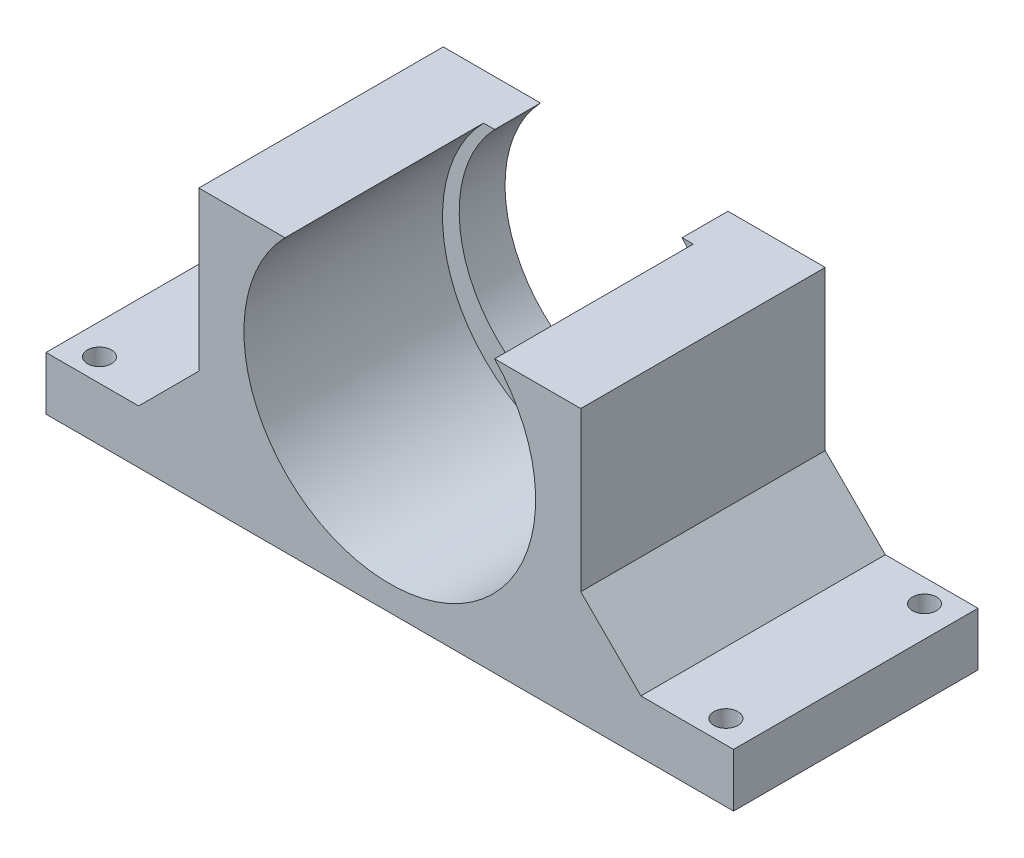
SolidWorks part; units mm, degrees
material "PF"
ref_plane "Front Plane" through (0, 0, 0) normal (0, 0, 1) x (1, 0, 0)
ref_plane "Top Plane" through (0, 0, 0) normal (0, 1, 0) x (1, 0, 0)
ref_plane "Right Plane" through (0, 0, 0) normal (1, 0, 0) x (0, 0, -1)
sketch "Sketch1" plane through (0, 0, 0) normal (0, 0, 1) x (1, 0, 0)
  line L1 (-31.75, -30.48) -> (31.75, -30.48)
  line L2 (-31.75, -30.48) -> (-31.75, 30.48)
  line L3 (-31.75, 30.48) -> (31.75, 30.48)
  line L4 (31.75, -30.48) -> (31.75, 30.48)
  line L5 (-31.75, -30.48) -> (31.75, 30.48) construction
  line L6 (-31.75, 30.48) -> (31.75, -30.48) construction
  point P0 (0, 0)
  dimension "D1" = 63.5
  dimension "D2" = 60.96
extrude "Boss-Extrude1" add sketch "Sketch1" along normal blind 40.64
sketch "Sketch2" plane through (0, 0, 40.64) normal (0, 0, 1) x (1, 0, 0)
  line L0 (0, -30.48) -> (0, -26.33)
  line L1 (-31.75, -30.48) -> (31.75, -30.48) construction
  line L3 (-10.3896, 27.3176) -> (10.3896, 27.3176)
  line L4 (-10.3896, 27.3176) -> (-10.3896, 23.2174)
  line L5 (-10.3896, 23.2174) -> (10.3896, 23.2174)
  line L6 (10.3896, 27.3176) -> (10.3896, 23.2174)
  line L7 (-10.3896, 27.3176) -> (10.3896, 23.2174) construction
  line L8 (-10.3896, 23.2174) -> (10.3896, 27.3176) construction
  circle A0 centre (0, -2.08) radius 24.25
  point P7 (0, 25.2675)
  dimension "D1" = 48.5
  dimension "D2" = 4.15
extrude "Cut-Extrude1" cut sketch "Sketch2" against normal blind 33.02 contours A0
sketch "Sketch8" plane through (0, 30.48, 0) normal (0, 1, 0) x (1, 0, 0)
  line L1 (-31.75, -40.64) -> (31.75, -40.64)
  line L2 (-31.75, -40.64) -> (-31.75, 0)
  line L3 (-31.75, 0) -> (31.75, 0)
  line L4 (31.75, -40.64) -> (31.75, 0)
extrude "Cut-Extrude3" cut sketch "Sketch8" against normal blind 15.6972
sketch "Sketch11" plane through (0, 0, 0) normal (0, 0, -1) x (-1, 0, 0)
  circle A0 centre (0, 0) radius 21.4786
sketch "Sketch16" plane through (0, -30.48, 0) normal (0, -1, 0) x (1, 0, 0)
  line L1 (-31.75, 40.64) -> (-57.15, 40.64)
  line L2 (-31.75, 40.64) -> (-31.75, 0)
  line L3 (-31.75, 0) -> (-57.15, 0)
  line L4 (-57.15, 40.64) -> (-57.15, 0)
  line L5 (31.75, 40.64) -> (57.15, 40.64)
  line L6 (31.75, 40.64) -> (31.75, 0)
  line L7 (31.75, 0) -> (57.15, 0)
  line L8 (57.15, 40.64) -> (57.15, 0)
  dimension "D1" = 25.4
  dimension "D2" = 25.4
extrude "Boss-Extrude5" add sketch "Sketch16" against normal blind 8.89
sketch "Sketch17" plane through (0, -21.59, 0) normal (0, 1, 0) x (1, 0, 0)
  line L0 (-57.15, 0) -> (-31.75, 0) construction
  line L1 (-57.15, -40.64) -> (-57.15, 0) construction
  line L2 (-31.75, -40.64) -> (-57.15, -40.64) construction
  line L4 (57.15, 0) -> (57.15, -40.64) construction
  circle A0 centre (-52.07, -3.81) radius 2
  circle A1 centre (-52.07, -36.83) radius 2
  circle A2 centre (52.07, -3.81) radius 2
  circle A3 centre (52.07, -36.83) radius 2
  dimension "D1" = 4
  dimension "D2" = 3.81
  dimension "D3" = 5.08
  dimension "D4" = 3.81
  dimension "D5" = 5.08
  dimension "D6" = 5.08
  dimension "D7" = 5.08
extrude "Cut-Extrude5" cut sketch "Sketch17" against normal through all
extrude "Cut-Extrude6" cut sketch "Sketch11" against normal through all
chamfer "Chamfer1" distance 10 angle 45 2 edges at (-31.75, -21.59, 20.32) (31.75, -21.59, 20.32)
